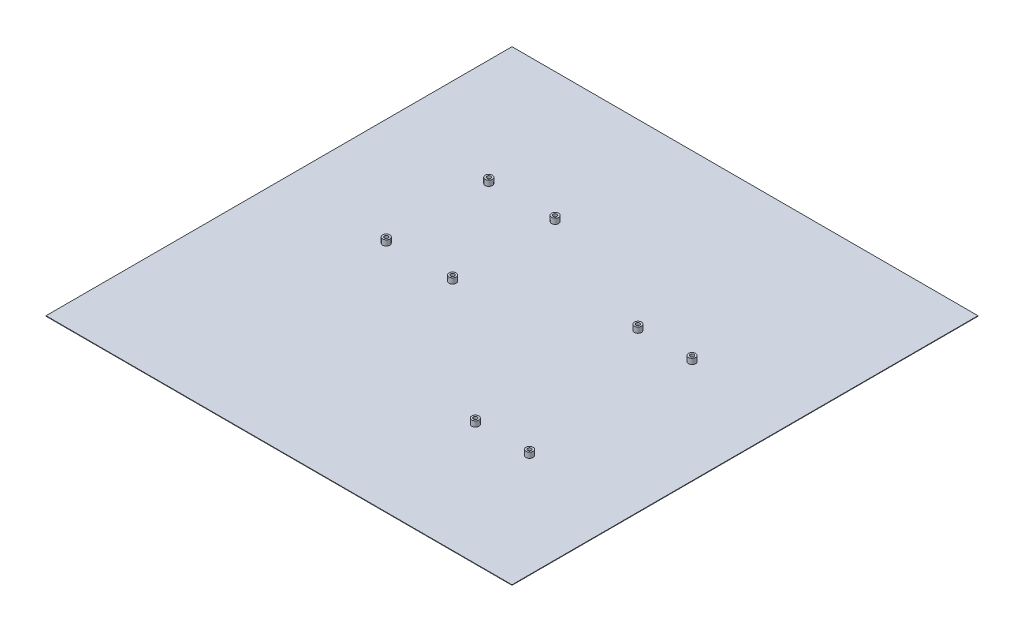
SolidWorks part; units mm, degrees
ref_plane "Front Plane" through (0, 0, 0) normal (0, 0, 1) x (1, 0, 0)
ref_plane "Top Plane" through (0, 0, 0) normal (0, 1, 0) x (1, 0, 0)
ref_plane "Right Plane" through (0, 0, 0) normal (1, 0, 0) x (0, 0, -1)
sketch "Sketch1" plane through (0, 0, 0) normal (0, 1, 0) x (1, 0, 0)
  line L1 (-215, -215) -> (215, -215)
  line L2 (-215, -215) -> (-215, 215)
  line L3 (-215, 215) -> (215, 215)
  line L4 (215, -215) -> (215, 215)
  line L5 (-215, -215) -> (215, 215) construction
  line L6 (-215, 215) -> (215, -215) construction
  point P0 (0, 0)
  dimension "D1" = 430
  dimension "D2" = 430
extrude "Boss-Extrude1" add sketch "Sketch1" along normal blind 0.45
sketch "Sketch6" plane through (0, 0.45, 0) normal (0, 1, 0) x (1, 0, 0)
  circle A0 centre (119.7933, 46.3731) radius 3.3
  circle A1 centre (69.7933, 46.3731) radius 3.3
  circle A2 centre (119.7933, -103.6269) radius 3.3
  circle A3 centre (69.7933, -103.6269) radius 3.3
sketch "Sketch7" plane through (0, 0.45, 0) normal (0, 1, 0) x (1, 0, 0)
  circle A0 centre (-116.3627, 94.9459) radius 3.3
  circle A1 centre (-55.3632, 95.1916) radius 3.3
  circle A2 centre (-54.9804, 0.1924) radius 3.3
  circle A3 centre (-115.98, -0.0534) radius 3.3
extrude "Boss-Extrude2" add sketch "Sketch7" along normal blind 5
sketch "Sketch8" plane through (0, 5.45, 0) normal (0, 1, 0) x (1, 0, 0)
  circle A0 centre (-54.9804, 0.1924) radius 1.75
  circle A1 centre (-55.3632, 95.1916) radius 1.75
  circle A2 centre (-116.3627, 94.9459) radius 1.75
  circle A3 centre (-115.98, -0.0534) radius 1.75
extrude "Cut-Extrude1" cut sketch "Sketch8" against normal blind 4
extrude "Boss-Extrude3" add sketch "Sketch6" along normal blind 5
sketch "Sketch10" plane through (0, 5.45, 0) normal (0, 1, 0) x (1, 0, 0)
  circle A0 centre (69.7933, 46.3731) radius 1.75
  circle A1 centre (119.7933, 46.3731) radius 1.75
  circle A2 centre (119.7933, -103.6269) radius 1.75
  circle A3 centre (69.7933, -103.6269) radius 1.75
extrude "Cut-Extrude2" cut sketch "Sketch10" against normal blind 4
